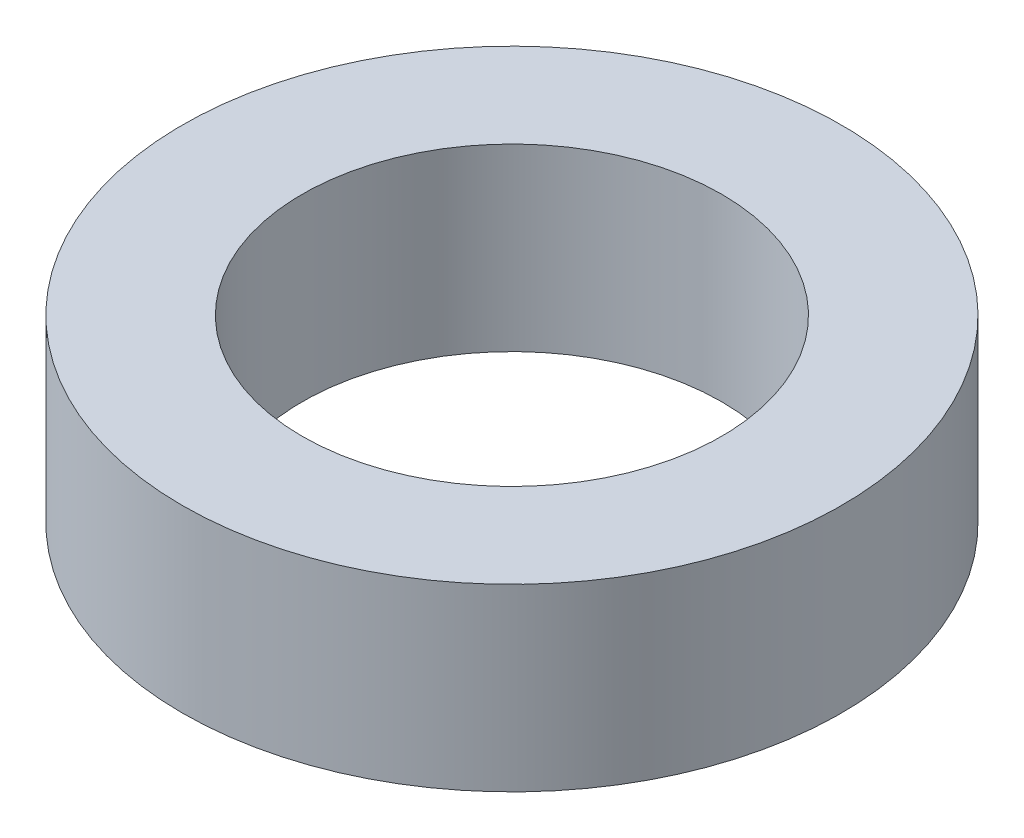
SolidWorks part; units mm, degrees
ref_plane "前视基准面" through (0, 0, 0) normal (0, 0, 1) x (1, 0, 0)
ref_plane "上视基准面" through (0, 0, 0) normal (0, 1, 0) x (1, 0, 0)
ref_plane "右视基准面" through (0, 0, 0) normal (1, 0, 0) x (0, 0, -1)
sketch "草图1" plane through (0, 0, 0) normal (0, 1, 0) x (1, 0, 0)
  circle A0 centre (0, 0) radius 3.5
  circle A1 centre (0, 0) radius 5.5
  dimension "D1" = 7
  dimension "D2" = 11
extrude "凸台-拉伸1" add sketch "草图1" along normal blind 3
